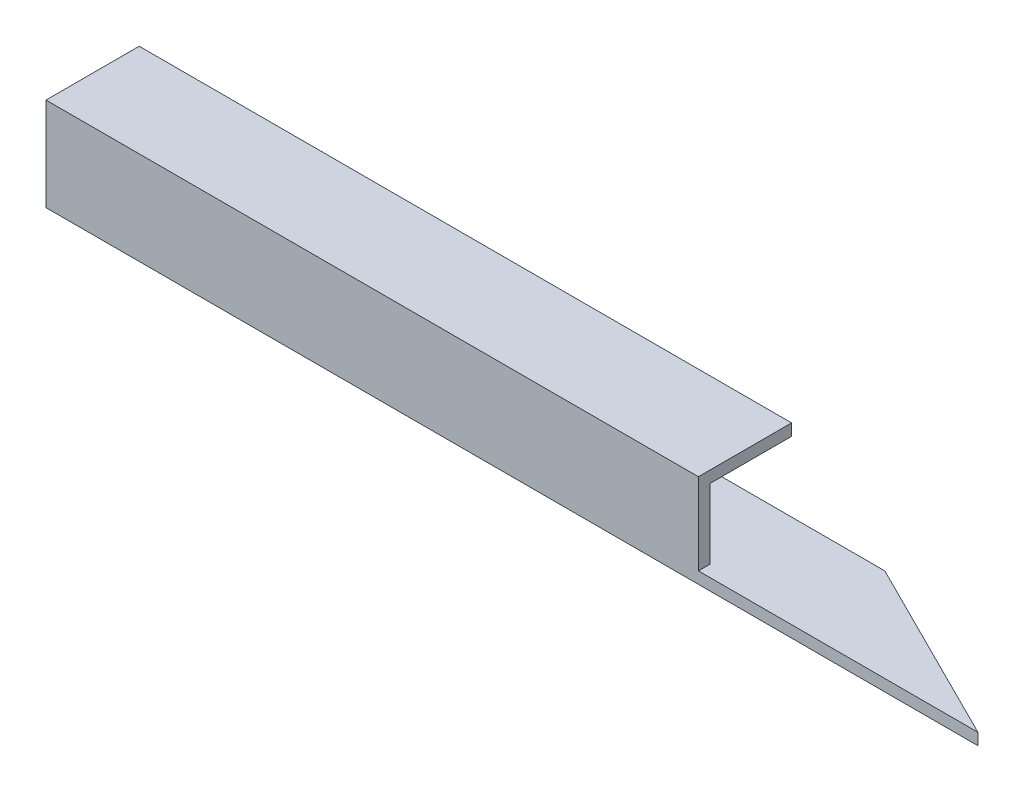
SolidWorks part; units mm, degrees
ref_plane "Front Plane" through (0, 0, 0) normal (0, 0, 1) x (1, 0, 0)
ref_plane "Top Plane" through (0, 0, 0) normal (0, 1, 0) x (1, 0, 0)
ref_plane "Right Plane" through (0, 0, 0) normal (1, 0, 0) x (0, 0, -1)
sketch "Sketch1" plane through (0, 0, 0) normal (0, 1, 0) x (1, 0, 0)
  line L0 (175.3595, -19.6248) -> (124.5595, 5.7752)
  line L1 (-78.6405, 5.7752) -> (175.3595, 5.7752)
  line L2 (-78.6405, 5.7752) -> (-78.6405, -19.6248)
  line L3 (-78.6405, -19.6248) -> (175.3595, -19.6248)
  line L4 (175.3595, 5.7752) -> (175.3595, -19.6248)
  dimension "D1" = 25.4
  dimension "D2" = 254
  dimension "D3" = 50.8
extrude "Boss-Extrude1" add sketch "Sketch1" along normal blind 25.4 contours L2 L3 L0 L1
sketch "Sketch2" plane through (-78.6405, 0, 0) normal (-1, 0, 0) x (0, 0, 1)
  line L0 (-5.7752, 25.4) -> (19.6248, 25.4) construction
  line L1 (-2.6002, 3.175) -> (16.4498, 3.175)
  line L2 (-2.6002, 3.175) -> (-2.6002, 22.225)
  line L3 (-2.6002, 22.225) -> (16.4498, 22.225)
  line L4 (16.4498, 3.175) -> (16.4498, 22.225)
  line L5 (-2.6002, 3.175) -> (16.4498, 22.225) construction
  line L6 (-2.6002, 22.225) -> (16.4498, 3.175) construction
  line L7 (19.6248, 25.4) -> (19.6248, 0) construction
  line L8 (-5.7752, 25.4) -> (-5.7752, 0) construction
  line L9 (-5.7752, 0) -> (19.6248, 0) construction
  point P0 (6.9248, 12.7)
  point P9 (-5.7752, 12.7)
  dimension "D1" = 3.175
  dimension "D2" = 3.175
  dimension "D3" = 3.175
  dimension "D4" = 3.175
extrude "Cut-Extrude1" cut sketch "Sketch2" against normal through all
sketch "Sketch3" plane through (0, 25.4, 0) normal (0, 1, 0) x (1, 0, 0)
  line L0 (99.1595, -19.6248) -> (99.1595, 5.7752)
  line L1 (-78.6405, 5.7752) -> (124.5595, 5.7752) construction
  line L2 (-78.6405, -19.6248) -> (175.3595, -19.6248) construction
  line L3 (99.1595, 5.7752) -> (124.5595, 5.7752)
  line L4 (124.5595, 5.7752) -> (175.3595, -19.6248)
  line L5 (175.3595, -19.6248) -> (99.1595, -19.6248)
  line L7 (-78.6405, 5.7752) -> (-78.6405, -19.6248)
  line L8 (-78.6405, -19.6248) -> (175.3595, -19.6248)
  line L9 (175.3595, -19.6248) -> (124.5595, 5.7752)
  line L10 (124.5595, 5.7752) -> (-78.6405, 5.7752)
  line L11 (-78.6405, 5.7752) -> (-78.6405, -19.6248)
  line L12 (-78.6405, -19.6248) -> (99.1595, -19.6248)
  line L14 (99.1595, 5.7752) -> (-78.6405, 5.7752)
  dimension "D2" = 76.2
  dimension "D3" = 25.4
  dimension "D1" = 0
extrude "Cut-Extrude2" cut sketch "Sketch3" against normal blind 22.225
sketch "Sketch5" plane through (0, 0, -5.7752) normal (0, 0, -1) x (-1, 0, 0)
  line L0 (-99.1595, 25.4) -> (-99.1595, 3.175)
  line L1 (-99.1595, 3.175) -> (78.6405, 3.175)
  line L2 (78.6405, 25.4) -> (78.6405, 0) construction
  line L3 (78.6405, 3.175) -> (78.6405, 22.225)
  line L4 (78.6405, 22.225) -> (-99.1595, 22.225)
  line L5 (78.6405, 25.4) -> (-99.1595, 25.4) construction
  line M6 (78.6405, 0) -> (78.6405, 25.4)
  dimension "D1" = 3.175
extrude "Cut-Extrude4" cut sketch "Sketch5" against normal blind 22.225 contours L4 L0 L1 M6
